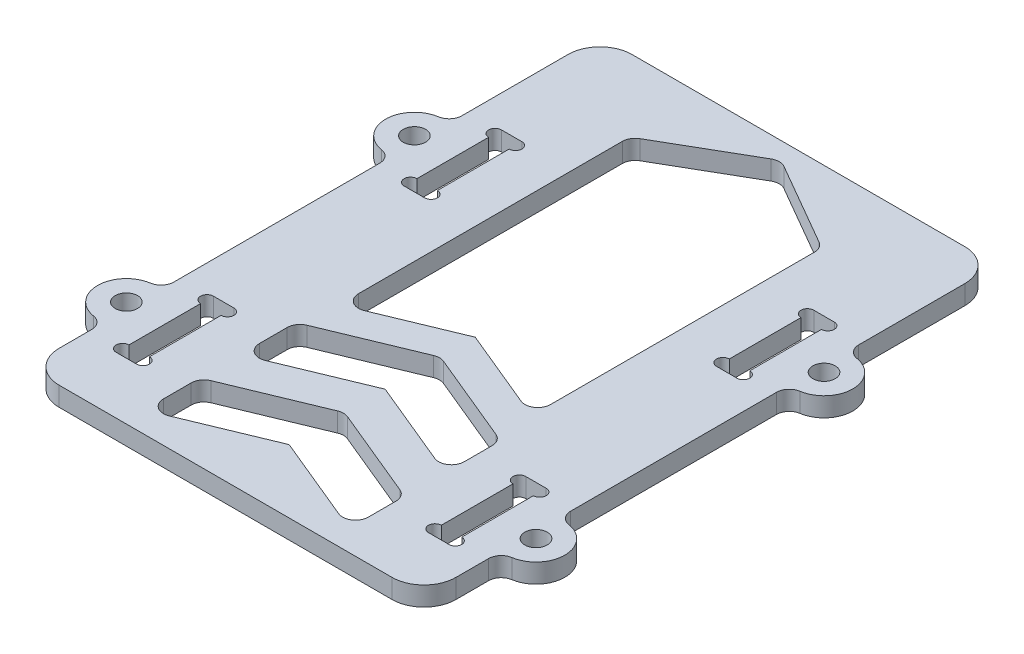
SolidWorks part; units mm, degrees
material "环氧树脂,未充填"
ref_plane "前视基准面" through (0, 0, 0) normal (0, 0, 1) x (1, 0, 0)
ref_plane "上视基准面" through (0, 0, 0) normal (0, 1, 0) x (1, 0, 0)
ref_plane "右视基准面" through (0, 0, 0) normal (1, 0, 0) x (0, 0, -1)
sketch "草图1" plane through (0, 0, 0) normal (0, 1, 0) x (1, 0, 0)
  line L0 (-42, 39) -> (42, 39)
  line L5 (44, 37) -> (44, 33)
  line L6 (42, 31) -> (33, 31)
  line L7 (-40, 35) -> (40, 35) construction
  line L8 (-40, 35) -> (-40, -35) construction
  line L9 (-40, -35) -> (40, -35) construction
  line L10 (40, 35) -> (40, -35) construction
  line L11 (-40, 35) -> (40, -35) construction
  line L12 (-40, -35) -> (40, 35) construction
  line L13 (31, 29) -> (31, -29)
  line L14 (33, -31) -> (42, -31)
  line L15 (44, -33) -> (44, -37)
  line L16 (42, -39) -> (-42, -39)
  line L17 (-44, -37) -> (-44, -33)
  line L18 (-42, -31) -> (-33, -31)
  line L19 (-31, -29) -> (-31, 29)
  line L20 (-33, 31) -> (-42, 31)
  line L21 (-44, 33) -> (-44, 37)
  line L22 (-22.8, -993.8794) -> (-22.8, 14.9) construction
  line L23 (23, -997.6117) -> (23, 49002.3883) construction
  line L24 (0, -1000) -> (0, 49000) construction
  line L25 (-1000, 0) -> (49000, 0) construction
  line L26 (-22.8, 30.1) -> (-22.8, 49006.1206) construction
  line L27 (-22.8, 30.1) -> (-26, 30.1)
  line L28 (-22.8, 28.1) -> (-22.8, 16.9)
  line L29 (-22.8, 14.9) -> (-26, 14.9)
  line L30 (-26, 28.1) -> (-26, 16.9)
  line L31 (-22.8, 30.1) -> (-26, 14.9) construction
  line L32 (-22.8, 14.9) -> (-26, 30.1) construction
  line L33 (-22.8, 16.9) -> (-22.8, 28.1) construction
  line L34 (22.8, 30.1) -> (26, 30.1)
  line L35 (22.8, 28.1) -> (22.8, 16.9)
  line L36 (22.8, 14.9) -> (26, 14.9)
  line L37 (26, 28.1) -> (26, 16.9)
  line L38 (22.8, -30.1) -> (26, -30.1)
  line L39 (22.8, -28.1) -> (22.8, -16.9)
  line L40 (22.8, -14.9) -> (26, -14.9)
  line L41 (26, -28.1) -> (26, -16.9)
  line L42 (-22.8, -30.1) -> (-26, -30.1)
  line L43 (-22.8, -28.1) -> (-22.8, -16.9)
  line L44 (-22.8, -14.9) -> (-26, -14.9)
  line L45 (-26, -28.1) -> (-26, -16.9)
  circle A0 centre (-40, 35) radius 1.65
  circle A1 centre (40, 35) radius 1.65
  circle A2 centre (-40, -35) radius 1.65
  circle A3 centre (40, -35) radius 1.65
  arc A4 (-42, 39) -> (-44, 37) centre (-42, 37) ccw
  arc A5 (-42, 31) -> (-44, 33) centre (-42, 33) cw
  arc A6 (42, 39) -> (44, 37) centre (42, 37) cw
  arc A7 (44, 33) -> (42, 31) centre (42, 33) cw
  arc A8 (42, -31) -> (44, -33) centre (42, -33) cw
  arc A9 (44, -37) -> (42, -39) centre (42, -37) cw
  arc A10 (-44, -33) -> (-42, -31) centre (-42, -33) cw
  arc A11 (-42, -39) -> (-44, -37) centre (-42, -37) cw
  arc A12 (-26, 30.1) -> (-26, 28.1) centre (-26, 29.1) ccw
  arc A13 (-22.8, 28.1) -> (-22.8, 30.1) centre (-22.8, 29.1) ccw
  arc A14 (-22.8, 14.9) -> (-22.8, 16.9) centre (-22.8, 15.9) ccw
  arc A15 (-26, 16.9) -> (-26, 14.9) centre (-26, 15.9) ccw
  arc A16 (26, 30.1) -> (26, 28.1) centre (26, 29.1) cw
  arc A17 (22.8, 28.1) -> (22.8, 30.1) centre (22.8, 29.1) cw
  arc A18 (22.8, 14.9) -> (22.8, 16.9) centre (22.8, 15.9) cw
  arc A19 (26, 16.9) -> (26, 14.9) centre (26, 15.9) cw
  arc A20 (22.8, -28.1) -> (22.8, -30.1) centre (22.8, -29.1) ccw
  arc A21 (22.8, -14.9) -> (22.8, -16.9) centre (22.8, -15.9) ccw
  arc A22 (26, -16.9) -> (26, -14.9) centre (26, -15.9) ccw
  arc A23 (26, -30.1) -> (26, -28.1) centre (26, -29.1) ccw
  arc A24 (-26, -30.1) -> (-26, -28.1) centre (-26, -29.1) cw
  arc A25 (-22.8, -28.1) -> (-22.8, -30.1) centre (-22.8, -29.1) cw
  arc A26 (-22.8, -14.9) -> (-22.8, -16.9) centre (-22.8, -15.9) cw
  arc A27 (-26, -16.9) -> (-26, -14.9) centre (-26, -15.9) cw
  arc A28 (33, 31) -> (31, 29) centre (33, 29) ccw
  arc A29 (31, -29) -> (33, -31) centre (33, -29) ccw
  arc A30 (-33, -31) -> (-31, -29) centre (-33, -29) ccw
  arc A31 (-31, 29) -> (-33, 31) centre (-33, 29) ccw
  point P4 (0, 0)
  point P11 (0, 0)
  point P22 (-44, -35)
  point P23 (-44, 35)
  point P38 (-44, -31)
  point P41 (-44, -39)
  point P54 (-24.4, 22.5)
  dimension "D4" = 3.3
  dimension "D6" = 2
  dimension "D7" = 4
  dimension "D13" = 2
  dimension "D15" = 2
  dimension "D1" = 8
  dimension "D2" = 80
  dimension "D3" = 70
  dimension "D5" = 4
  dimension "D8" = 45.8
  dimension "D9" = 23
  dimension "D10" = 3.2
  dimension "D11" = 15.2
  dimension "D12" = 14.9
  dimension "D14" = 5
extrude "凸台-拉伸1" add sketch "草图1" along normal blind 3
sketch "草图3" plane through (0, 3, 0) normal (0, 1, 0) x (1, 0, 0)
  line L0 (42, 39) -> (-42, 39) construction
  line L1 (-31, 50.5) -> (31, 50.5)
  line L2 (-31, 50.5) -> (-31, 39)
  line L3 (-31, 39) -> (31, 39)
  line L4 (31, 50.5) -> (31, 39)
  line L5 (-31, 50.5) -> (31, 39) construction
  line L6 (-31, 39) -> (31, 50.5) construction
  line L7 (31, -29) -> (31, 29) construction
  line L8 (-31, 29) -> (-31, -29) construction
  point P0 (0, 44.75)
  dimension "D1" = 11.5
extrude "凸台-拉伸2" add sketch "草图3" against normal blind 3
fillet "圆角1" radius 5 4 edges at (31, 1.5, -50.5) (31, 1.5, -39) (-31, 1.5, -39) (-31, 1.5, -50.5)
sketch "草图2" plane through (0, 3, 0) normal (0, 1, 0) x (1, 0, 0)
  line L0 (-1, 47.2321) -> (-14, 39.7265)
  line L1 (-15, 37.9944) -> (-15, -3.22)
  line L2 (-12.2346, -5.0678) -> (0, 0)
  line L3 (0, 0) -> (12.2346, -5.0678)
  line L4 (15, -3.22) -> (15, 37.9944)
  line L5 (14, 39.7265) -> (1, 47.2321)
  line L7 (-0.7654, -5.729) -> (-14.7654, -11.528)
  line L8 (-16, -13.3757) -> (-16, -17.7053)
  line L9 (-13.2346, -19.5531) -> (0, -14.0711)
  line L10 (0, -14.0711) -> (13.2346, -19.5531)
  line L11 (16, -17.7053) -> (16, -13.3757)
  line L12 (14.7654, -11.528) -> (0.7654, -5.729)
  line L13 (31, -29) -> (31, 29) construction
  line L14 (14.7654, -26.528) -> (0.7654, -20.729)
  line L15 (-0.7654, -20.729) -> (-14.7654, -26.528)
  line L16 (-16, -28.3757) -> (-16, -32.7053)
  line L17 (-13.2346, -34.5531) -> (0, -29.0711)
  line L18 (0, -29.0711) -> (13.2346, -34.5531)
  line L19 (16, -32.7053) -> (16, -28.3757)
  line L20 (26, 50.5) -> (-26, 50.5) construction
  arc A0 (-15, -3.22) -> (-12.2346, -5.0678) centre (-13, -3.22) ccw
  arc A1 (12.2346, -5.0678) -> (15, -3.22) centre (13, -3.22) ccw
  arc A2 (15, 37.9944) -> (14, 39.7265) centre (13, 37.9944) ccw
  arc A3 (-1, 47.2321) -> (1, 47.2321) centre (0, 45.5) cw
  arc A4 (-14, 39.7265) -> (-15, 37.9944) centre (-13, 37.9944) ccw
  arc A5 (-16, -17.7053) -> (-13.2346, -19.5531) centre (-14, -17.7053) ccw
  arc A6 (-14.7654, -11.528) -> (-16, -13.3757) centre (-14, -13.3757) ccw
  arc A7 (-0.7654, -5.729) -> (0.7654, -5.729) centre (0, -7.5767) cw
  arc A8 (13.2346, -19.5531) -> (16, -17.7053) centre (14, -17.7053) ccw
  arc A9 (16, -13.3757) -> (14.7654, -11.528) centre (14, -13.3757) ccw
  arc A10 (16, -28.3757) -> (14.7654, -26.528) centre (14, -28.3757) ccw
  arc A11 (-0.7654, -20.729) -> (0.7654, -20.729) centre (0, -22.5767) cw
  arc A12 (-14.7654, -26.528) -> (-16, -28.3757) centre (-14, -28.3757) ccw
  arc A13 (-16, -32.7053) -> (-13.2346, -34.5531) centre (-14, -32.7053) ccw
  arc A14 (13.2346, -34.5531) -> (16, -32.7053) centre (14, -32.7053) ccw
  point P17 (15, 39.1491)
  point P20 (0, 47.8094)
  point P23 (-15, 39.1491)
  dimension "D5" = 2
  dimension "D10" = 2
  dimension "D11" = 2
  dimension "D12" = 2
  dimension "D1" = 30
  dimension "D2" = 135
  dimension "D3" = 120
  dimension "D4" = 5
  dimension "D6" = 5
  dimension "D7" = 5
  dimension "D8" = 8
  dimension "D9" = 15
  dimension "D14" = 15
  dimension "D13" = 2
extrude "切除-拉伸1" cut sketch "草图2" against normal blind 10
sketch "草图4" plane through (0, 3, 0) normal (0, 1, 0) x (1, 0, 0)
  line L1 (-32, -22.5) -> (32, -22.5) construction
  line L2 (-32, -22.5) -> (-32, 22.5) construction
  line L3 (-32, 22.5) -> (32, 22.5) construction
  line L4 (32, -22.5) -> (32, 22.5) construction
  line L5 (-32, -22.5) -> (32, 22.5) construction
  line L6 (-32, 22.5) -> (32, -22.5) construction
  circle A0 centre (32, 22.5) radius 1.75
  circle A1 centre (-32, 22.5) radius 1.75
  circle A2 centre (-32, -22.5) radius 1.75
  circle A3 centre (32, -22.5) radius 1.75
  circle A4 centre (-32, 22.5) radius 4.5
  circle A5 centre (32, 22.5) radius 4.5
  circle A6 centre (32, -22.5) radius 4.5
  circle A7 centre (-32, -22.5) radius 4.5
  point P0 (0, 0)
  dimension "D3" = 3.5
  dimension "D4" = 9
  dimension "D1" = 64
  dimension "D2" = 45
extrude "凸台-拉伸3" add sketch "草图4" against normal blind 3
fillet "圆角2" radius 2 8 edges at (31, 1.5, 26.8875) (31, 1.5, 18.1125) (31, 1.5, -18.1125) (31, 1.5, -26.8875) (-31, 1.5, -26.8875) (-31, 1.5, -18.1125) (-31, 1.5, 18.1125) (-31, 1.5, 26.8875)
sketch "草图5" plane through (0, 3, 0) normal (0, 1, 0) x (1, 0, 0)
  line L0 (-1000, 0) -> (49000, 0) construction
  line L1 (-32, 22.5) -> (32, -22.5) construction
  line L2 (0, -1000) -> (0, 49000) construction
  circle A0 centre (-32, 22.5) radius 1.75
  circle A1 centre (32, 22.5) radius 1.75
  circle A2 centre (32, -22.5) radius 1.75
  circle A3 centre (-32, -22.5) radius 1.75
  point P8 (0, 0)
  dimension "D1" = 3.5
extrude "切除-拉伸2" cut sketch "草图5" against normal blind 3
sketch "草图6" plane through (0, 3, 0) normal (0, 1, 0) x (1, 0, 0)
  line L0 (-31, 45.5) -> (-31, 28.9226)
  line L1 (-31, 28.9226) -> (-44.5272, 28.9226)
  line L2 (-44.5272, 28.9226) -> (-44.5272, -29)
  line L3 (-44.5272, -29) -> (-31, -29)
  line L4 (-31, -29) -> (-31, -39)
  line L5 (-42, -39) -> (42, -39) construction
  line L6 (-31, -39) -> (31, -39)
  line L7 (31, -39) -> (31, -28.9226)
  line L8 (31, -28.9226) -> (42.8522, -28.9226)
  line L9 (42.8522, -28.9226) -> (42.8522, 29)
  line L10 (42.8522, 29) -> (31, 29)
  line L11 (31, 29) -> (31, 45.5)
  line L12 (31, 45.5) -> (31, 52.1886)
  line L13 (31, 52.1886) -> (-31, 52.1886)
  line L14 (-31, 52.1886) -> (-31, 45.5)
extrude "切除-拉伸4" cut sketch "草图6" against normal blind 10 flip side to cut
fillet "圆角3" radius 5 2 edges at (-31, 1.5, 39) (31, 1.5, 39)
